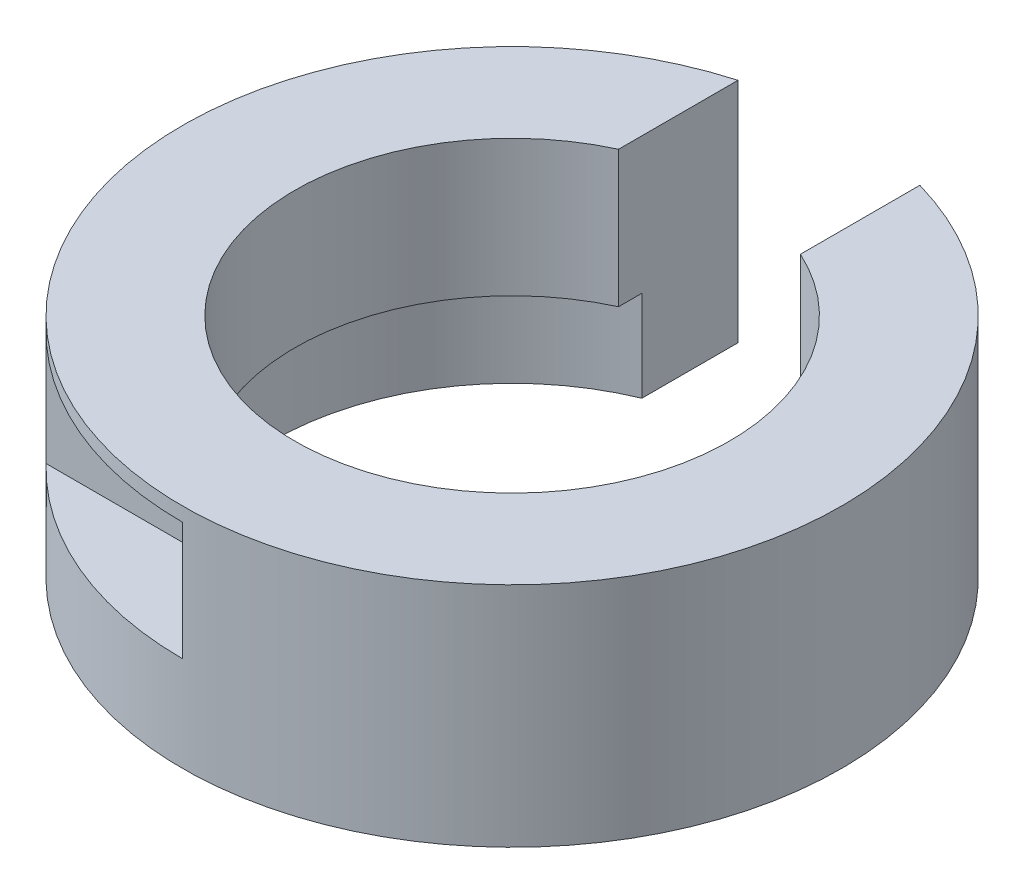
SolidWorks part; units mm, degrees
ref_plane "Plano frontal" through (0, 0, 0) normal (0, 0, 1) x (1, 0, 0)
ref_plane "Plano superior" through (0, 0, 0) normal (0, 1, 0) x (1, 0, 0)
ref_plane "Plano direito" through (0, 0, 0) normal (1, 0, 0) x (0, 0, -1)
sketch "Esboço1" plane through (0, 0, 0) normal (0, 1, 0) x (1, 0, 0)
  circle A0 centre (0, 0) radius 52.5
  circle A1 centre (0, 0) radius 72.5
  dimension "D1" = 105
  dimension "D2" = 20
extrude "Ressalto-extrusão1" add sketch "Esboço1" along normal blind 50 contours A1 A0 | A0
sketch "Esboço2" plane through (0, 50, 0) normal (0, 1, 0) x (1, 0, 0)
  line L0 (0, 0) -> (0, 97.357) construction
  line L1 (20, 0) -> (-20, 0)
  line L2 (-20, 0) -> (-20, 97.357)
  line L3 (-20, 97.357) -> (20, 97.357)
  line L4 (20, 0) -> (20, 97.357)
  dimension "D1" = 20
  dimension "D2" = 97.357
extrude "Corte-extrusão1" cut sketch "Esboço2" against normal through all both and the other way through all
sketch "Esboço3" plane through (0, 50, 0) normal (0, 1, 0) x (1, 0, 0)
  circle A0 centre (0, 0) radius 47.8
  circle A1 centre (0, 0) radius 52.5
  dimension "D1" = 95.6
  dimension "D2" = 105
extrude "Ressalto-extrusão2" add sketch "Esboço3" against normal blind 30
sketch "Esboço4" plane through (0, 50, 0) normal (0, 1, 0) x (1, 0, 0)
  line L0 (-20, 69.6868) -> (-20, 29.7554)
  line L1 (-20, 29.7554) -> (20, 29.7554)
  line L2 (20, 29.7554) -> (20, 73.6653)
  line L3 (20, 73.6653) -> (-20, 73.6653)
  line L4 (-20, 73.6653) -> (-20, 69.6868)
extrude "Corte-extrusão2" cut sketch "Esboço4" against normal through all both and the other way through all
sketch "Esboço5" plane through (0, 0, 0) normal (1, 0, 0) x (0, 0, -1)
  line L0 (-73.4675, 46.905) -> (-50.3238, 46.905)
  line L1 (-50.3238, 46.905) -> (-50.3238, 20.905)
  line L2 (-50.3238, 20.905) -> (-73.4675, 20.905)
  line L3 (-73.4675, 20.905) -> (-73.4675, 46.905)
  point P2 (-73.4675, 20.905)
  dimension "D1" = 26
extrude "Corte-extrusão3" cut sketch "Esboço5" against normal through all
